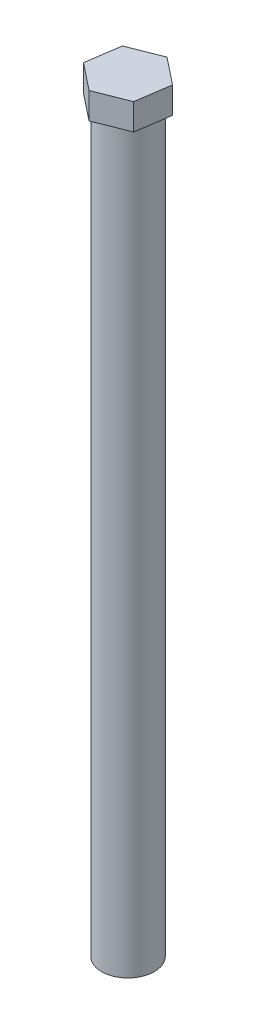
SolidWorks part; units mm, degrees
ref_plane "Front Plane" through (0, 0, 0) normal (0, 0, 1) x (1, 0, 0)
ref_plane "Top Plane" through (0, 0, 0) normal (0, 1, 0) x (1, 0, 0)
ref_plane "Right Plane" through (0, 0, 0) normal (1, 0, 0) x (0, 0, -1)
sketch "Sketch1" plane through (0, 0, 0) normal (0, 1, 0) x (1, 0, 0)
  circle A0 centre (0, 0) radius 2
  dimension "D1" = 4
extrude "Boss-Extrude1" add sketch "Sketch1" along normal blind 56
sketch "Sketch2" plane through (0, 56, 0) normal (0, 1, 0) x (1, 0, 0)
  line L1 (2.04, -1.6157) -> (2.4192, 0.9588)
  line L2 (2.4192, 0.9588) -> (0.3792, 2.5745)
  line L3 (0.3792, 2.5745) -> (-2.04, 1.6157)
  line L4 (-2.04, 1.6157) -> (-2.4192, -0.9588)
  line L5 (-2.4192, -0.9588) -> (-0.3792, -2.5745)
  line L6 (-0.3792, -2.5745) -> (2.04, -1.6157)
  circle A0 centre (0, 0) radius 2.2537 construction
extrude "Boss-Extrude2" add sketch "Sketch2" along normal blind 2
